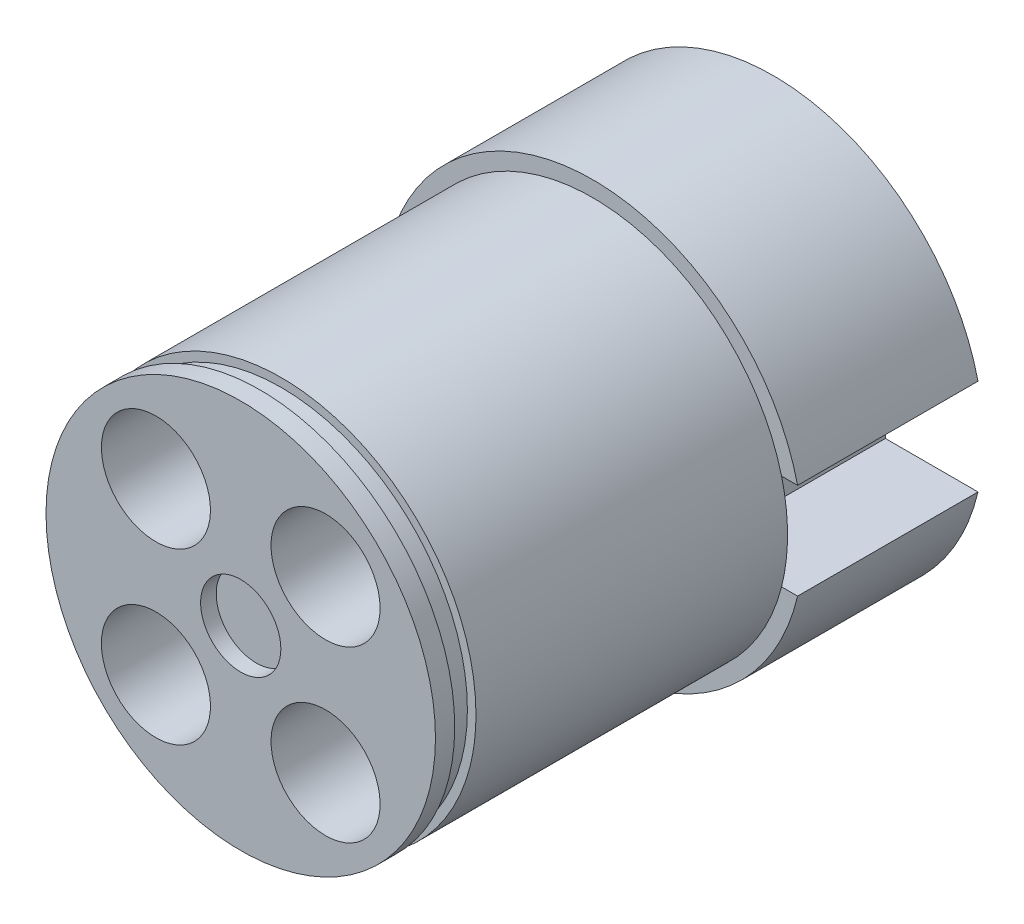
SolidWorks part; units mm, degrees
ref_plane "Front Plane" through (0, 0, 0) normal (0, 0, 1) x (1, 0, 0)
ref_plane "Top Plane" through (0, 0, 0) normal (0, 1, 0) x (1, 0, 0)
ref_plane "Right Plane" through (0, 0, 0) normal (1, 0, 0) x (0, 0, -1)
ref_axis "Z" through (0, 0, 24.309) along (0, 0, -1)
sketch "Sketch1" plane through (0, 0, 0) normal (0, 0, 1) x (1, 0, 0)
  circle A0 centre (0, 0) radius 12.5
  dimension "D1" = 25
extrude "Boss-Extrude1" add sketch "Sketch1" along normal blind 22.6
sketch "Sketch2" plane through (0, 0, 0) normal (0, 0, 1) x (1, 0, 0)
  circle A0 centre (0, 0) radius 13.5
  dimension "D1" = 27
extrude "Boss-Extrude2" add sketch "Sketch2" against normal blind 11.58
sketch "Sketch9" plane through (0, 0, 0) normal (1, 0, 0) x (0, 0, -1)
  line L0 (0, 0) -> (-20, 0) construction
  line L1 (-20, 0) -> (-20, -12.5) construction
  line L2 (-20, -12.5) -> (-21.365, -12.5)
  line L3 (-21.365, -12.5) -> (-21.365, -11.95)
  line L4 (-21.365, -11.95) -> (-20, -11.95)
  line L5 (-20, -11.95) -> (-20, -12.5)
  dimension "D1" = 20
  dimension "D2" = 25
  dimension "D3" = 1.365
  dimension "D4" = 23.9
revolve "Cut-Revolve1" cut sketch "Sketch9" angle 360 about axis through (0, 0, 24.309) along (0, 0, -1)
sketch "Sketch4" plane through (0, 0, 22.6) normal (0, 0, 1) x (1, 0, 0)
  circle A0 centre (0, 0) radius 2.575
  dimension "D1" = 5.15
extrude "MagnetSlot" cut sketch "Sketch4" against normal blind 1
sketch "Sketch6" plane through (0, 0, 22.6) normal (0, 0, 1) x (1, 0, 0)
  line L0 (0, 0) -> (5.4447, 5.4447) construction
  line L1 (0, 0) -> (0, 18.4845) construction
  line L2 (6.2068, 8.2889) -> (3.3627, 7.5268)
  line L3 (3.3627, 7.5268) -> (2.6006, 4.6826)
  line L4 (2.6006, 4.6826) -> (4.6826, 2.6006)
  line L5 (4.6826, 2.6006) -> (7.5268, 3.3627)
  line L6 (7.5268, 3.3627) -> (8.2889, 6.2068)
  line L7 (8.2889, 6.2068) -> (6.2068, 8.2889)
  circle A0 centre (5.4447, 5.4447) radius 2.55 construction
  dimension "D1" = 7.7
  dimension "D2" = 5.1
  dimension "D3" = 45
extrude "NutCut" cut sketch "Sketch6" against normal offset from surface (30.18 mm away) 4 up to face at (13.5, 0, -11.58)
sketch "Sketch7" plane through (0, 0, 22.6) normal (0, 0, 1) x (1, 0, 0)
  circle A0 centre (5.4447, 5.4447) radius 3.5
  dimension "D1" = 7
extrude "NutHole" cut sketch "Sketch7" against normal blind 15
sketch "Sketch8" plane through (0, 0, 22.6) normal (0, 0, 1) x (1, 0, 0)
  circle A0 centre (5.4447, 5.4447) radius 1.35
  dimension "D1" = 2.7
extrude "ScrewHole" cut sketch "Sketch8" against normal through all both and the other way through all
pattern_circular "CirPattern1" count 4 over 360 about axis through (0, 0, 0) along (0, 0, 1) of "MagnetSlot", "NutCut", "NutHole", "ScrewHole"
ref_plane "Plane1" through (7.2, 0, 0) normal (1, 0, 0) x (0, 0, -1)
sketch "Sketch11" plane through (7.2, 0, 0) normal (1, 0, 0) x (0, 0, -1)
  line L0 (0, 12.5) -> (0, -12.5) construction
  line L1 (15.4735, 3.0775) -> (0, 3.0775)
  line L2 (15.4735, 3.0775) -> (15.4735, -3.0775)
  line L3 (15.4735, -3.0775) -> (0, -3.0775)
  line L4 (0, 3.0775) -> (0, -3.0775)
  line L5 (16.9247, 0) -> (30.6852, 0) construction
extrude "Cut-Extrude1" cut sketch "Sketch11" along normal through all
equation "\"BearingBaseDistance\"= 12"
equation "\"BearingOD\"= 32"
equation "\"BearingHeight\"= 4"
equation "\"SeatsOD\"= \"BearingOD\" + 10"
equation "\"WireHarnessHeight\"= 0.05in * 4 + 4.5"
equation "\"OuterWallWidth\"= 6"
equation "\"OverallOD\" = 50"
equation "\"RetainingRingThickness\" = 1.30"
equation "\"RetaininRingGrooveDiameter\" = 23.9"
equation "\"ShaftLengthAfterFlange\" = 2*\"BearingHeight\" + \"BearingBaseDistance\" + \"RetainingRingThickness\"*2\t'give a retaining ring thickness of extra clearance"
equation "\"RetainingRingGrooveBase\" = \"ShaftLengthAfterFlange\" - \"RetainingRingThickness\"*2"
equation "\"BearingID\" = 25"
equation "\"CoverClearance\" = 1"
equation "\"CoverThickness\" = 1"
equation "\"FlangHeight\" = \"CoverThickness\" + \"CoverClearance\" + \"WireHarnessHeight\""
equation "\"D1@Sketch1\"=\"BearingID\""
equation "\"D2@Sketch9\"=\"BearingID\""
equation "\"D3@Sketch9\"=\"RetainingRingThickness\"*1.05"
equation "\"D4@Sketch9\"=\"RetaininRingGrooveDiameter\""
equation "\"D1@Boss-Extrude2\"=\"FlangHeight\""
equation "\"D1@Sketch9\"=\"RetainingRingGrooveBase\""
equation "\"D1@Boss-Extrude1\"=\"ShaftLengthAfterFlange\""
